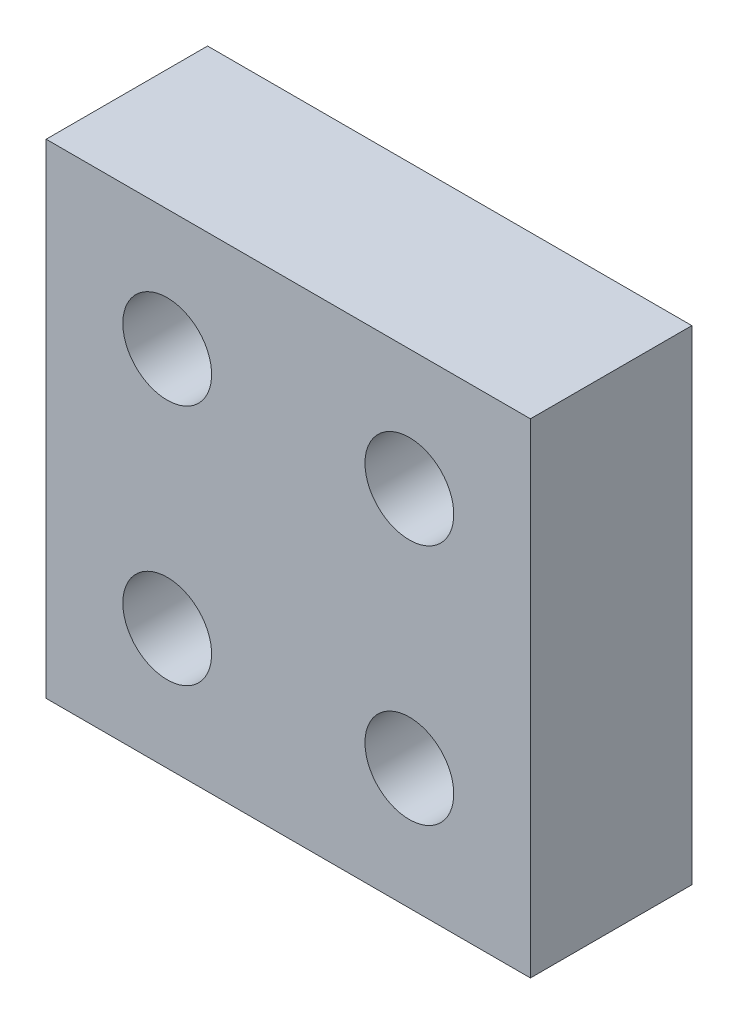
SolidWorks part; units mm, degrees
ref_plane "Front Plane" through (0, 0, 0) normal (0, 0, 1) x (1, 0, 0)
ref_plane "Top Plane" through (0, 0, 0) normal (0, 1, 0) x (1, 0, 0)
ref_plane "Right Plane" through (0, 0, 0) normal (1, 0, 0) x (0, 0, -1)
ref_plane "Plane1" through (0, 0, 8) normal (0, 0, 1) x (1, 0, 0)
sketch "Sketch1" plane through (0, 0, 8) normal (0, 0, 1) x (1, 0, 0)
  line L0 (-12, 12) -> (-12, -12)
  line L1 (-12, -12) -> (12, -12)
  line L2 (12, -12) -> (12, 12)
  line L3 (12, 12) -> (-12, 12)
  circle A0 centre (-6, -6) radius 2.2
  circle A1 centre (6, 6) radius 2.2
  circle A2 centre (6, -6) radius 2.2
  circle A3 centre (-6, 6) radius 2.2
extrude "Boss-Extrude1" add sketch "Sketch1" against normal blind 8
